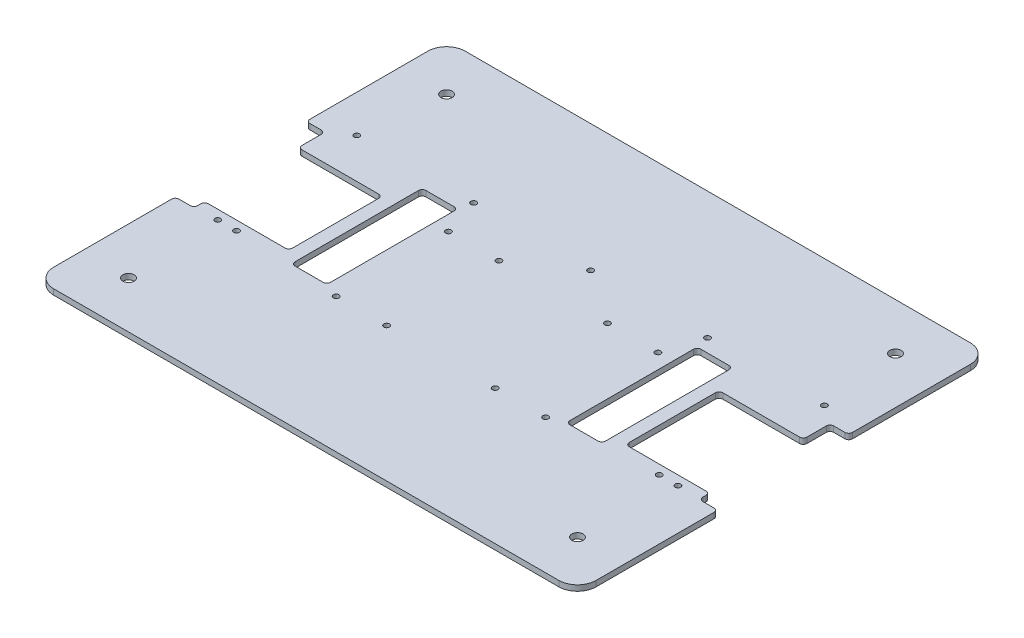
SolidWorks part; units mm, degrees
material "Акрил (Средняя-высокая ударопрочность)"
ref_plane "Спереди" through (0, 0, 0) normal (0, 0, 1) x (1, 0, 0)
ref_plane "Сверху" through (0, 0, 0) normal (0, 1, 0) x (1, 0, 0)
ref_plane "Справа" through (0, 0, 0) normal (1, 0, 0) x (0, 0, -1)
sketch "Эскиз1" plane through (0, 0, 0) normal (0, 1, 0) x (1, 0, 0)
  line L1 (-145, 110) -> (145, 110)
  line L2 (-145, 110) -> (-145, -110)
  line L3 (-145, -110) -> (145, -110)
  line L4 (145, 110) -> (145, -110)
  line L5 (-145, 110) -> (145, -110) construction
  line L6 (-145, -110) -> (145, 110) construction
  point P0 (0, 0)
  dimension "D1" = 290
  dimension "D2" = 220
extrude "Бобышка-Вытянуть1" add sketch "Эскиз1" along normal blind 3
sketch "Эскиз2" plane through (0, 3, 0) normal (0, 1, 0) x (1, 0, 0)
  line L0 (0, 0) -> (-145, 0) construction
  line L1 (-145, 110) -> (-145, -110) construction
  line L2 (0, 0) -> (0, 110) construction
  line L3 (145, 110) -> (-145, 110) construction
  line L4 (135, -35) -> (145, -35)
  line L5 (-135, -35) -> (-145, -35)
  line L6 (-135, -35) -> (-135, -29.3)
  line L7 (-135, 35) -> (-145, 35)
  line L8 (-145, -35) -> (-145, 35)
  line L9 (-135, -35) -> (-145, 35) construction
  line L10 (-135, 35) -> (-145, -35) construction
  line L11 (145, -35) -> (145, 35)
  line L12 (135, 35) -> (145, 35)
  line L13 (135, -35) -> (135, -29.3)
  line L14 (-118, -4.3) -> (-118, -34.3) construction
  line L15 (-113, -34.3) -> (-123, -34.3) construction
  line L16 (-135, 20.7) -> (-135, 35)
  line L17 (-90, 20.7) -> (-135, 20.7)
  line L18 (-90, 20.7) -> (-90, -29.3)
  line L19 (-90, -29.3) -> (-135, -29.3)
  line L20 (90, -29.3) -> (135, -29.3)
  line L21 (-135, 20.7) -> (-90, -29.3) construction
  line L22 (-135, -29.3) -> (-90, 20.7) construction
  line L23 (90, 20.7) -> (90, -29.3)
  line L24 (90, 20.7) -> (135, 20.7)
  line L25 (135, 20.7) -> (135, 35)
  line L26 (83, -35) -> (64, -35)
  line L27 (-83, 35) -> (-64, 35)
  line L28 (-83, 35) -> (-83, -35)
  line L29 (-83, -35) -> (-64, -35)
  line L30 (-64, 35) -> (-64, -35)
  line L31 (-83, 35) -> (-64, -35) construction
  line L32 (-83, -35) -> (-64, 35) construction
  line L33 (83, 35) -> (83, -35)
  line L34 (83, 35) -> (64, 35)
  line L35 (64, 35) -> (64, -35)
  line L36 (-118, -4.3) -> (-112.5, -4.3) construction
  line L37 (-56, -38) -> (-29, -38) construction
  line L38 (-29, -38) -> (-29, 22) construction
  line L39 (-29, 22) -> (-56, 22) construction
  line L40 (-56, 22) -> (-56, -38) construction
  line L41 (0, 42) -> (-62.5, 42) construction
  line L43 (-62.5, 42) -> (-125, 42) construction
  line L44 (-120, -85) -> (-120, -110) construction
  line L45 (-145, -110) -> (145, -110) construction
  line L46 (-120, -85) -> (-145, -85) construction
  line L47 (-120, 85) -> (-120, 110) construction
  line L48 (-120, 85) -> (-145, 85) construction
  circle A0 centre (-123, -34.3) radius 1.5
  circle A1 centre (-113, -34.3) radius 1.5
  circle A2 centre (123, -34.3) radius 1.5
  circle A3 centre (113, -34.3) radius 1.5
  circle A4 centre (-56, -38) radius 1.5
  circle A5 centre (-29, -38) radius 1.5
  circle A6 centre (-56, 22) radius 1.5
  circle A7 centre (-29, 22) radius 1.5
  circle A8 centre (56, -38) radius 1.5
  circle A9 centre (29, -38) radius 1.5
  circle A10 centre (29, 22) radius 1.5
  circle A11 centre (56, 22) radius 1.5
  circle A12 centre (-125, 42) radius 1.5
  circle A13 centre (-62.5, 42) radius 1.5
  circle A14 centre (0, 42) radius 1.5
  circle A15 centre (125, 42) radius 1.5
  circle A16 centre (62.5, 42) radius 1.5
  circle A17 centre (-120, 85) radius 3
  circle A18 centre (-120, -85) radius 3
  circle A19 centre (120, 85) radius 3
  circle A20 centre (120, -85) radius 3
  point P5 (-140, 0)
  point P35 (-112.5, -4.3)
  point P36 (-73, 0)
  point P45 (-73.5, 0)
  dimension "D3" = 3
  dimension "D13" = 3
  dimension "D19" = 3
  dimension "D23" = 6
  dimension "D1" = 10
  dimension "D2" = 70
  dimension "D4" = 30
  dimension "D5" = 10
  dimension "D6" = 27
  dimension "D7" = 50
  dimension "D8" = 45
  dimension "D9" = 7
  dimension "D10" = 19
  dimension "D11" = 70
  dimension "D12" = 20.7
  dimension "D14" = 8
  dimension "D15" = 22
  dimension "D16" = 27
  dimension "D17" = 60
  dimension "D18" = 7
  dimension "D20" = 10
  dimension "D21" = 62.5
  dimension "D22" = 250
  dimension "D24" = 25
extrude "Вырез-Вытянуть1" cut sketch "Эскиз2" against normal through all
fillet "Скругление1" radius 10 4 edges at (145, 1.5, 110) (-145, 1.5, 110) (-145, 1.5, -110) (145, 1.5, -110)
fillet "Скругление2" radius 2 24 edges at (-64, 1.5, -35) (-90, 1.5, -20.7) (-135, 1.5, -35) (-83, 1.5, -35) (-135, 1.5, -20.7) (-145, 1.5, -35) (-83, 1.5, 35) (-64, 1.5, 35) (-90, 1.5, 29.3) (-135, 1.5, 29.3) (-135, 1.5, 35) (-145, 1.5, 35) (135, 1.5, 29.3) (135, 1.5, 35) (145, 1.5, 35) (145, 1.5, -35) (135, 1.5, -35) (135, 1.5, -20.7) (83, 1.5, -35) (64, 1.5, -35) (90, 1.5, -20.7) (90, 1.5, 29.3) (83, 1.5, 35) (64, 1.5, 35)
